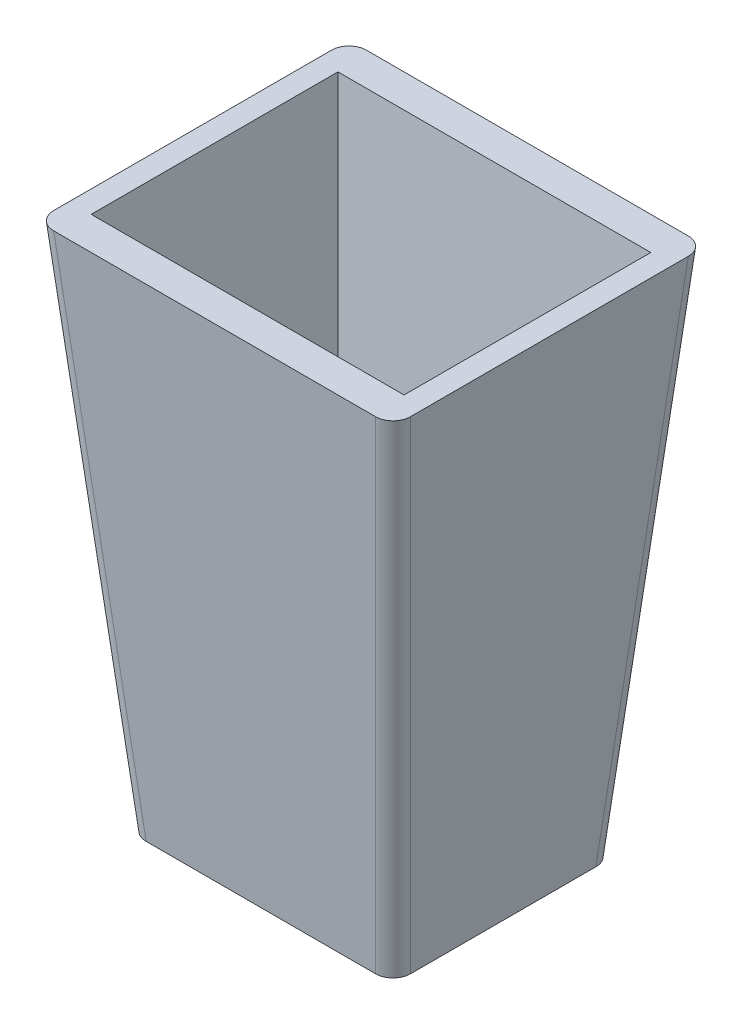
SolidWorks part; units mm, degrees
ref_plane "Front Plane" through (0, 0, 0) normal (0, 0, 1) x (1, 0, 0)
ref_plane "Top Plane" through (0, 0, 0) normal (0, 1, 0) x (1, 0, 0)
ref_plane "Right Plane" through (0, 0, 0) normal (1, 0, 0) x (0, 0, -1)
sketch "Sketch1" plane through (0, 0, 0) normal (0, 1, 0) x (1, 0, 0)
  line L7 (-19.05, -15.875) -> (19.05, -15.875)
  line L8 (-19.05, -15.875) -> (-19.05, 15.875)
  line L9 (-19.05, 15.875) -> (19.05, 15.875)
  line L10 (19.05, -15.875) -> (19.05, 15.875)
  line L11 (-19.05, -15.875) -> (19.05, 15.875) construction
  line L12 (-19.05, 15.875) -> (19.05, -15.875) construction
  point P6 (0, 0)
  dimension "D1" = 38.1
  dimension "D2" = 31.75
extrude "Boss-Extrude1" add sketch "Sketch1" along normal blind 76.2 draft 5 draft outward yes
sketch "Sketch3" plane through (0, 0, 0) normal (0, -1, 0) x (1, 0, 0)
  line L1 (-15.875, -11.1125) -> (15.875, -11.1125)
  line L2 (-15.875, -11.1125) -> (-15.875, 11.1125)
  line L3 (-15.875, 11.1125) -> (15.875, 11.1125)
  line L4 (15.875, -11.1125) -> (15.875, 11.1125)
  line L5 (-15.875, -11.1125) -> (15.875, 11.1125) construction
  line L6 (-15.875, 11.1125) -> (15.875, -11.1125) construction
  point P0 (0, 0)
  dimension "D1" = 31.75
  dimension "D2" = 22.225
extrude "Cut-Extrude1" cut sketch "Sketch3" against normal through all draft 5 draft outward yes
fillet "Fillet1" radius 2.54 4 edges at (-22.3833, 38.1, -19.2083) (-22.3833, 38.1, 19.2083) (22.3833, 38.1, 19.2083) (22.3833, 38.1, -19.2083)
